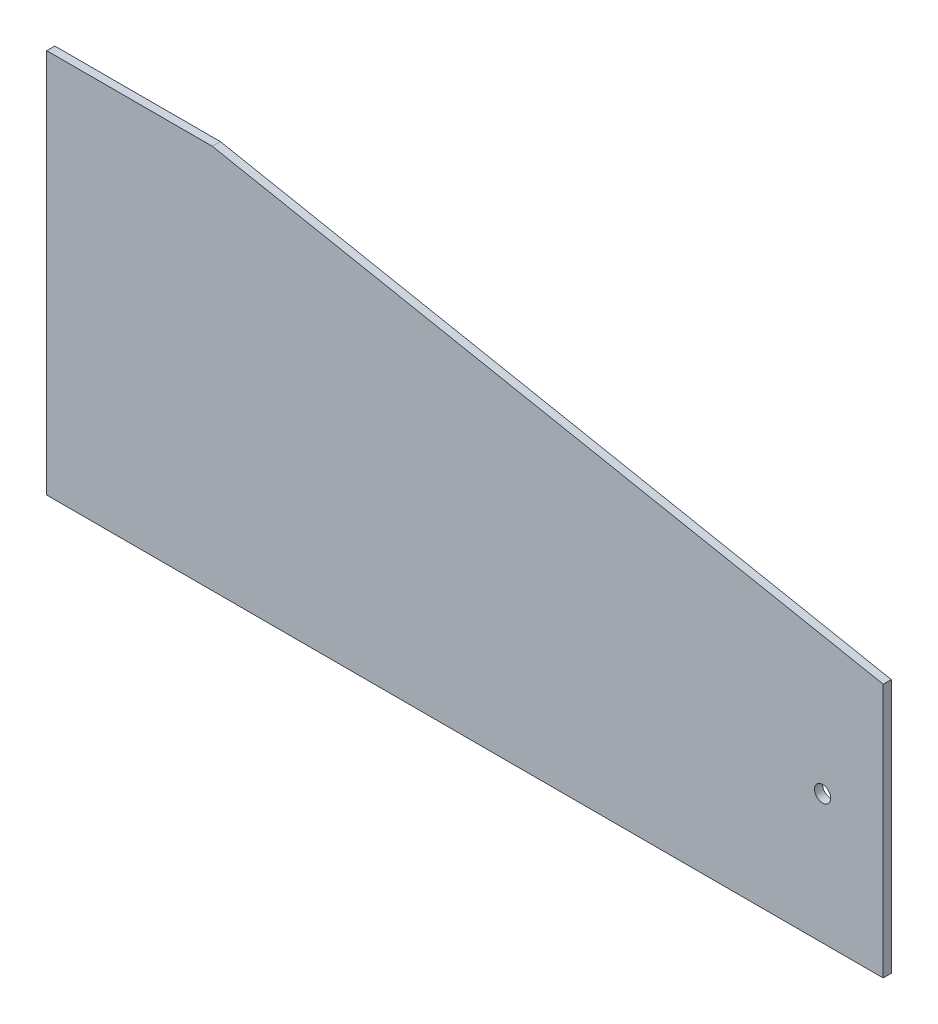
SolidWorks part; units mm, degrees
material "Pine"
ref_plane "Front Plane" through (0, 0, 0) normal (0, 0, 1) x (1, 0, 0)
ref_plane "Top Plane" through (0, 0, 0) normal (0, 1, 0) x (1, 0, 0)
ref_plane "Right Plane" through (0, 0, 0) normal (1, 0, 0) x (0, 0, -1)
sketch "Sketch1" plane through (0, 0, 0) normal (0, 0, 1) x (1, 0, 0)
  line L0 (0, 0) -> (0, 605)
  line L1 (0, 605) -> (260.3664, 605)
  line L2 (260.3664, 605) -> (1315, 400)
  line L3 (1315, 400) -> (1315, 0)
  line L4 (1315, 0) -> (0, 0)
  dimension "D1" = 90
  dimension "D2" = 79
  dimension "D3" = 400
  dimension "D4" = 1315
  dimension "D5" = 605
  dimension "D6" = 90
extrude "Boss-Extrude1" add sketch "Sketch1" along normal blind 12.7
sketch "Sketch2" plane through (0, 0, 12.7) normal (0, 0, 1) x (1, 0, 0)
  line L0 (1315, 0) -> (1315, 400) construction
  line L1 (0, 0) -> (1315, 0) construction
  circle A0 centre (1219.75, 203.2) radius 12.7
  dimension "D1" = 25.4
  dimension "D2" = 95.25
  dimension "D3" = 203.2
extrude "Cut-Extrude1" cut sketch "Sketch2" against normal blind 101.6
